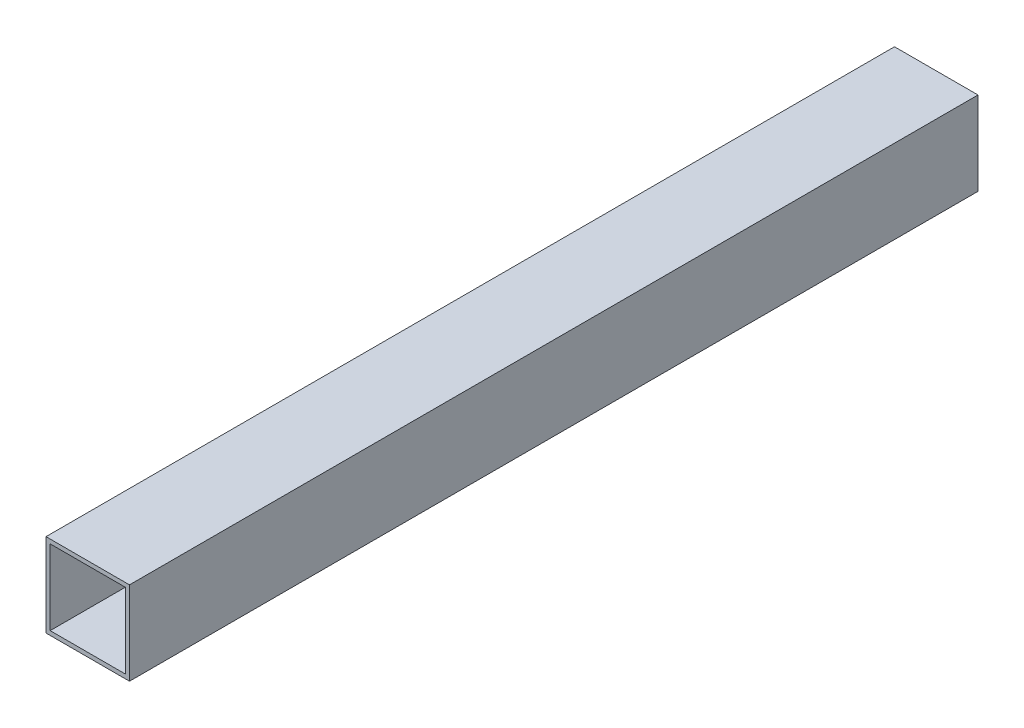
SolidWorks part; units mm, degrees
material "Aleación 1060"
ref_plane "Alzado" through (0, 0, 0) normal (0, 0, 1) x (1, 0, 0)
ref_plane "Planta" through (0, 0, 0) normal (0, 1, 0) x (1, 0, 0)
ref_plane "Vista lateral" through (0, 0, 0) normal (1, 0, 0) x (0, 0, -1)
sketch "Croquis1" plane through (0, 0, 0) normal (0, 0, 1) x (1, 0, 0)
  line L1 (20, -20) -> (-20, -20)
  line L2 (20, -20) -> (20, 20)
  line L3 (20, 20) -> (-20, 20)
  line L4 (-20, -20) -> (-20, 20)
  line L5 (20, -20) -> (-20, 20) construction
  line L6 (20, 20) -> (-20, -20) construction
  point P0 (0, 0)
  dimension "D1" = 40
  dimension "D2" = 40
extrude "Extruir-Lámina1" add sketch "Croquis1" along normal blind 406.5 thin
